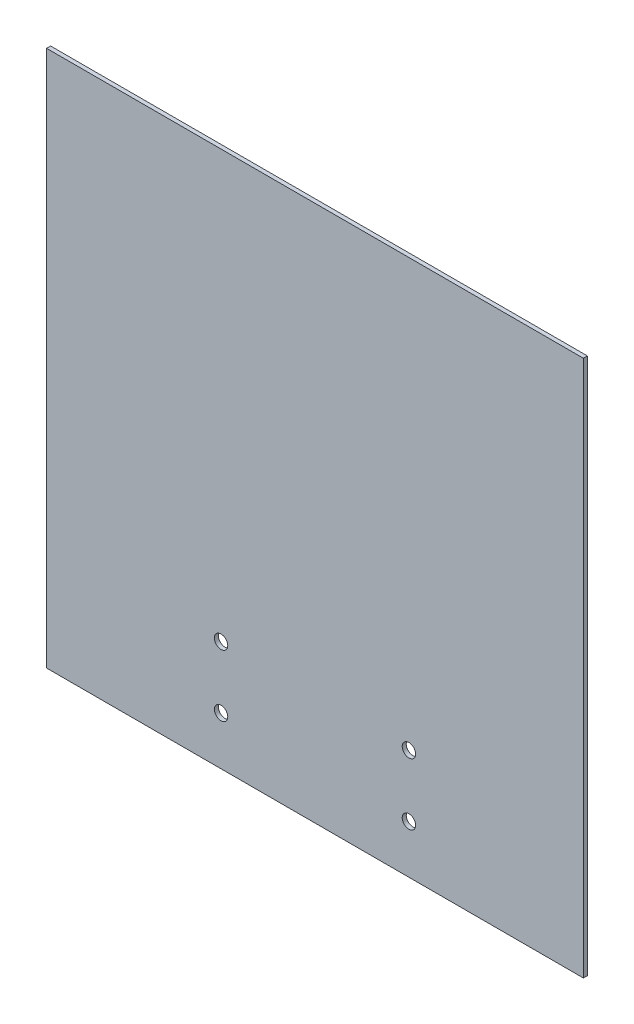
SolidWorks part; units mm, degrees
ref_plane "前视基准面" through (0, 0, 0) normal (0, 0, 1) x (1, 0, 0)
ref_plane "上视基准面" through (0, 0, 0) normal (0, 1, 0) x (1, 0, 0)
ref_plane "右视基准面" through (0, 0, 0) normal (1, 0, 0) x (0, 0, -1)
sketch "草图1" plane through (0, 0, 0) normal (0, 0, 1) x (1, 0, 0)
  line L1 (-100, -100) -> (100, -100)
  line L2 (-100, -100) -> (-100, 100)
  line L3 (-100, 100) -> (100, 100)
  line L4 (100, -100) -> (100, 100)
  line L5 (-100, -100) -> (100, 100) construction
  line L6 (-100, 100) -> (100, -100) construction
  point P0 (0, 0)
extrude "凸台-拉伸1" add sketch "草图1" along normal blind 1.5
sketch "草图2" plane through (0, 0, 1.5) normal (0, 0, 1) x (1, 0, 0)
  line L0 (-100, 100) -> (-100, -100) construction
  line L1 (0, 0) -> (0, -30) construction
  line L2 (-100, -100) -> (100, -100) construction
  line L3 (-35, -82) -> (-35, -59) construction
  circle A0 centre (-35, -82) radius 2.5
  circle A1 centre (-35, -59) radius 2.5
  circle A2 centre (35, -82) radius 2.5
  circle A3 centre (35, -59) radius 2.5
  dimension "D1" = 65
  dimension "D2" = 18
  dimension "D3" = 23
extrude "切除-拉伸1" cut sketch "草图2" against normal blind 1.5
